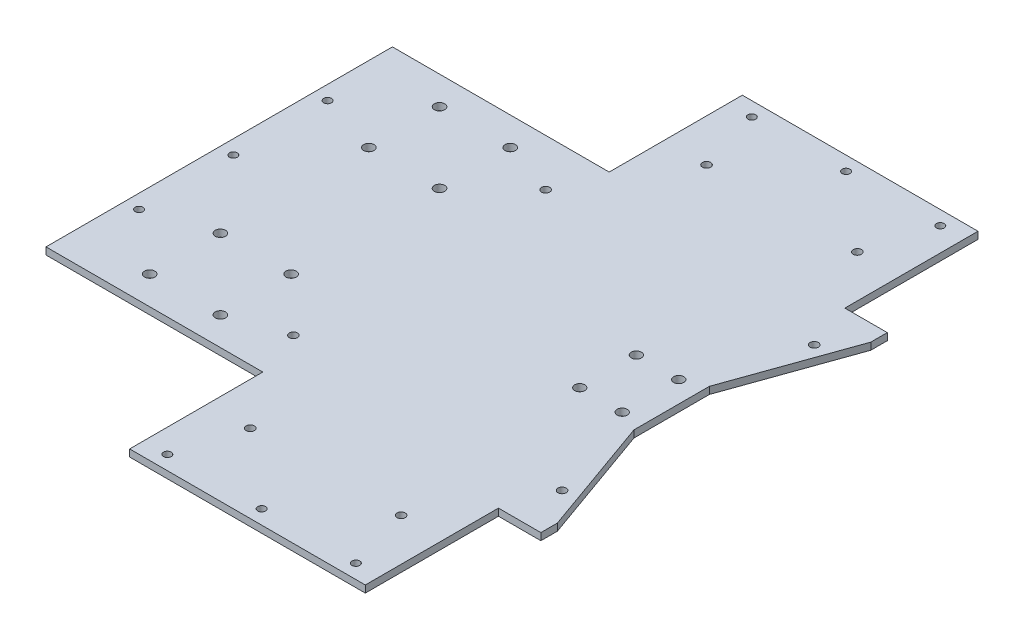
SolidWorks part; units mm, degrees
ref_plane "前视基准面" through (0, 0, 0) normal (0, 0, 1) x (1, 0, 0)
ref_plane "上视基准面" through (0, 0, 0) normal (0, 1, 0) x (1, 0, 0)
ref_plane "右视基准面" through (0, 0, 0) normal (1, 0, 0) x (0, 0, -1)
sketch "草图1" plane through (0, 0, 0) normal (0, 1, 0) x (1, 0, 0)
  line L0 (0, 72.5) -> (0, -35.361) construction
  line L1 (-105, -73.5) -> (-13, -73.5)
  line L2 (-105, -73.5) -> (-105, 73.5)
  line L3 (-105, 73.5) -> (-13, 73.5)
  line L4 (105, -73.5) -> (105, -66.5)
  line L5 (-105, 0) -> (204.6664, 0) construction
  line L6 (105, 66.5) -> (87, 16)
  line L7 (87, 16) -> (87, -16)
  line L8 (87, -16) -> (105, -66.5)
  line L9 (105, -66.5) -> (105, -73.5)
  line L10 (105, 66.5) -> (105, 73.5)
  line L11 (-13, 73.5) -> (-13, 130)
  line L12 (-13, 130) -> (87, 130)
  line L13 (87, 130) -> (87, 73.5)
  line L14 (87, -130) -> (87, -73.5)
  line L15 (-13, -130) -> (87, -130)
  line L16 (-13, -73.5) -> (-13, -130)
  line L17 (87, 73.5) -> (105, 73.5)
  line L18 (87, -73.5) -> (105, -73.5)
  dimension "D1" = 210
  dimension "D2" = 147
  dimension "D3" = 32
  dimension "D4" = 18
  dimension "D5" = 7
  dimension "D6" = 92
  dimension "D7" = 100
  dimension "D8" = 56.5
extrude "凸台-拉伸1" add sketch "草图1" along normal blind 3 contours L6 L10 L3 L2 L1 L4 L8 L7
sketch "草图2" plane through (0, 0, 0) normal (0, -1, 0) x (1, 0, 0)
  line L0 (-105, 0) -> (127.4355, 0) construction
  line L1 (-105, 73.5) -> (-105, -73.5) construction
  line L2 (87, -16) -> (87, 16) construction
  line L4 (-105, 73.5) -> (-13, 73.5) construction
  line L5 (-58, 100.4064) -> (-58, 41.6534) construction
  line L6 (-3, 124) -> (77, 124) construction
  line L7 (-13, 130) -> (87, 130) construction
  line L8 (37, 130) -> (37, 97.6295) construction
  circle A0 centre (78, -12) radius 2.15
  circle A1 centre (60, -12) radius 2.15
  circle A2 centre (60, 12) radius 2.15
  circle A3 centre (78, 12) radius 2.15
  circle A5 centre (-3, -124) radius 1.65
  circle A6 centre (37, -124) radius 1.65
  circle A7 centre (77, -124) radius 1.65
  circle A8 centre (77, 124) radius 1.65
  circle A9 centre (37, 124) radius 1.65
  circle A10 centre (-3, 124) radius 1.65
  circle A13 centre (-99, -40) radius 1.65
  circle A14 centre (-99, 40) radius 1.65
  circle A15 centre (-73, 61.5) radius 2.2
  circle A16 centre (-73, 31.5) radius 2.2
  circle A17 centre (-43, 61.5) radius 2.2
  circle A18 centre (-43, 31.5) radius 2.2
  circle A19 centre (-43, -31.5) radius 2.2
  circle A20 centre (-43, -61.5) radius 2.2
  circle A21 centre (-73, -31.5) radius 2.2
  circle A22 centre (-73, -61.5) radius 2.2
  circle A23 centre (-99, 0) radius 1.65
  dimension "D1" = 9
  dimension "D2" = 24
  dimension "D3" = 4.3
  dimension "D4" = 18
  dimension "D5" = 40
  dimension "D6" = 40
  dimension "D7" = 3.3
  dimension "D9" = 3.3
  dimension "D10" = 80
  dimension "D11" = 6
  dimension "D12" = 4.4
  dimension "D13" = 30
  dimension "D14" = 12
  dimension "D15" = 32
  dimension "D16" = 30
  dimension "D8" = 6
extrude "切除-拉伸1" cut sketch "草图2" against normal blind 10
sketch "草图3" plane through (0, 3, 0) normal (0, 1, 0) x (1, 0, 0)
  line L0 (-20.0027, 53.5) -> (4.9973, 96.8013) construction
  line L1 (-43, 53.5) -> (-20.0027, 53.5) construction
  line L2 (-105, 73.5) -> (-13, 73.5) construction
  line L4 (37, 124) -> (37, 56.1388) construction
  line L5 (0, 0) -> (39.5086, 0) construction
  circle A0 centre (-20.0027, 53.5) radius 1.75
  circle A1 centre (4.9973, 96.8013) radius 1.75
  circle A2 centre (69.0027, 96.8013) radius 1.75
  circle A3 centre (94.0027, 53.5) radius 1.75
  circle A4 centre (94.0027, -53.5) radius 1.75
  circle A5 centre (69.0027, -96.8013) radius 1.75
  circle A6 centre (4.9973, -96.8013) radius 1.75
  circle A7 centre (-20.0027, -53.5) radius 1.75
  point P0 (94.0027, 46.5)
  point P5 (-14.0756, 45.907)
  point P30 (-22.3974, 46.5)
  dimension "D2" = 120
  dimension "D1" = 50
  dimension "D3" = 20
extrude "切除-拉伸2" cut sketch "草图3" against normal blind 4.5
